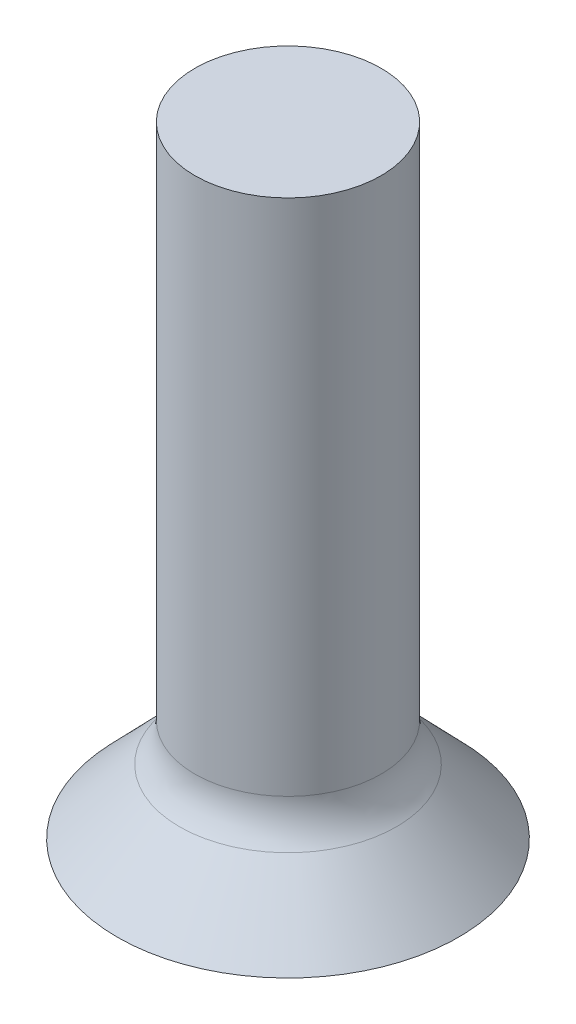
SolidWorks part; units mm, degrees
material "AISI 304"
ref_plane "前视基准面" through (0, 0, 0) normal (0, 0, 1) x (1, 0, 0)
ref_plane "上视基准面" through (0, 0, 0) normal (0, 1, 0) x (1, 0, 0)
ref_plane "右视基准面" through (0, 0, 0) normal (1, 0, 0) x (0, 0, -1)
sketch "草图1" plane through (0, 0, 0) normal (0, 0, 1) x (1, 0, 0)
  line L0 (0, 3.0955) -> (0, -2.4781) construction
  line L1 (0, 0) -> (2.75, 0)
  line L2 (2.75, 0) -> (1.747, 1.0386)
  line L3 (1.5, 1.65) -> (1.5, 10)
  line L4 (1.5, 10) -> (0, 10)
  line L5 (0, 10) -> (0, 0)
  arc A0 (1.5, 1.65) -> (1.747, 1.0386) centre (2.3801, 1.65) ccw
  dimension "D1" = 3
  dimension "D2" = 5.5
  dimension "D3" = 10
  dimension "D4" = 46
  dimension "D5" = 1.65
revolve "旋转1" add sketch "草图1" angle 360 about L0
sketch "草图2" plane through (0, 0, 0) normal (0, -1, 0) x (1, 0, 0)
  line L0 (-0.375, -0.375) -> (-0.375, -1.925)
  line L1 (-0.375, 1.925) -> (0.375, 1.925)
  line L2 (-0.375, 1.925) -> (-0.375, 0.375)
  line L3 (-0.375, -1.925) -> (0.375, -1.925)
  line L4 (0.375, 1.925) -> (0.375, 0.375)
  line L5 (-0.375, 1.925) -> (0.375, -1.925) construction
  line L6 (-0.375, -1.925) -> (0.375, 1.925) construction
  line L7 (-1.925, 0.375) -> (-0.375, 0.375)
  line L8 (-1.925, 0.375) -> (-1.925, -0.375)
  line L9 (-1.925, -0.375) -> (-0.375, -0.375)
  line L10 (1.925, 0.375) -> (1.925, -0.375)
  line L11 (-1.925, 0.375) -> (1.925, -0.375) construction
  line L12 (-1.925, -0.375) -> (1.925, 0.375) construction
  line L13 (0.375, 0.375) -> (1.925, 0.375)
  line L14 (0.375, -0.375) -> (0.375, -1.925)
  line L15 (0.375, -0.375) -> (1.925, -0.375)
  point P0 (0, 0)
  point P6 (0, 0)
  dimension "D1" = 0.75
  dimension "D2" = 3.85
extrude "切除-拉伸1" cut sketch "草图2" against normal blind 0.495
equation "\"螺钉直径\"= 3"
equation "\"螺钉头直径\"= 5.5"
equation "\"螺钉头厚度\"= 1.65"
equation "\"螺钉长度\"= 10"
equation "\"D1@草图1\"= \"螺钉直径\""
equation "\"D2@草图1\"= \"螺钉头直径\""
equation "\"D3@草图1\"= \"螺钉长度\""
equation "\"D5@草图1\"= \"螺钉头厚度\""
equation "\"D1@草图2\"= 0.25 * \"螺钉直径\""
equation "\"D2@草图2\"=0.7 *  \"螺钉头直径\""
equation "\"槽深\"= 0.3 * \"螺钉头厚度\""
equation "\"D1@切除-拉伸1\"= \"槽深\""
